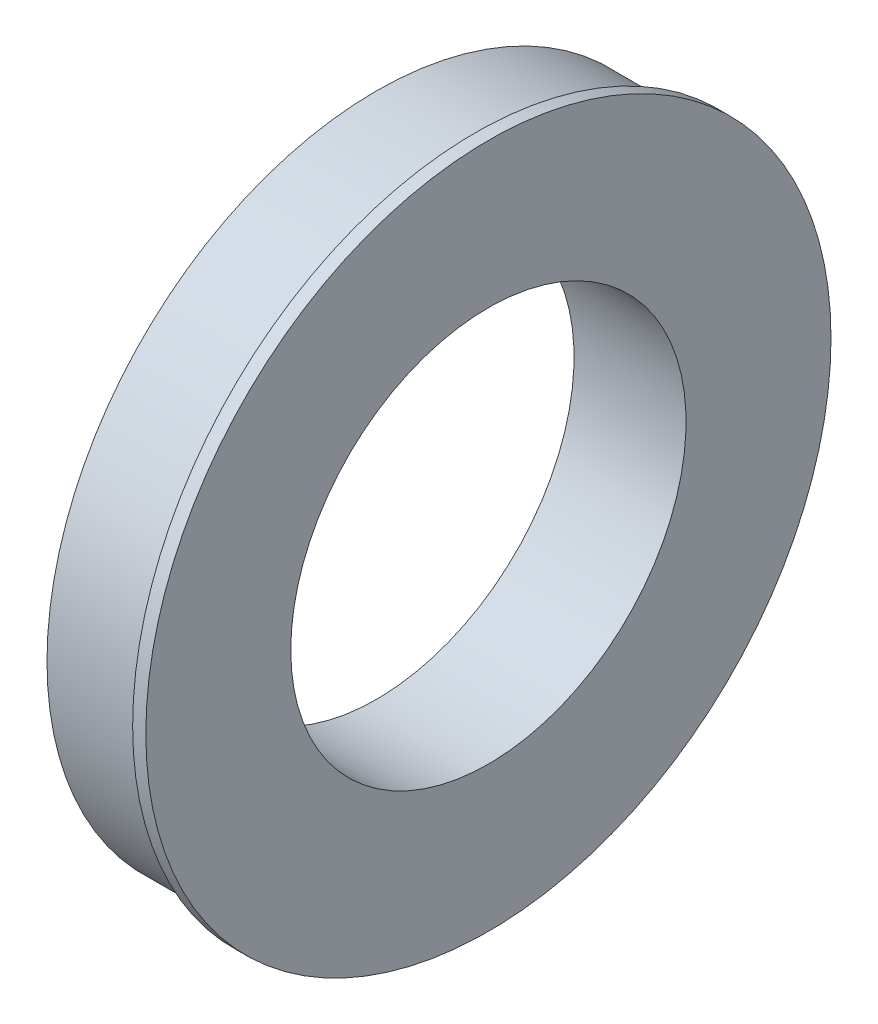
SolidWorks part; units mm, degrees
ref_plane "Front Plane" through (0, 0, 0) normal (0, 0, 1) x (1, 0, 0)
ref_plane "Top Plane" through (0, 0, 0) normal (0, 1, 0) x (1, 0, 0)
ref_plane "Right Plane" through (0, 0, 0) normal (1, 0, 0) x (0, 0, -1)
sketch "Sketch1" plane through (0, 0, 0) normal (1, 0, 0) x (0, 0, -1)
  circle A0 centre (0, 0) radius 63.5
  circle A1 centre (0, 0) radius 38.1
  dimension "D1" = 127
  dimension "D2" = 76.2
extrude "Boss-Extrude1" add sketch "Sketch1" along normal blind 19.05
sketch "Sketch3" plane through (19.05, 0, 0) normal (1, 0, 0) x (0, 0, -1)
  circle A0 centre (0, 0) radius 38.1 construction
  circle A1 centre (0, 0) radius 38.1
  circle A2 centre (0, 0) radius 66.04
  dimension "D1" = 132.08
extrude "Boss-Extrude2" add sketch "Sketch3" along normal blind 2.54
